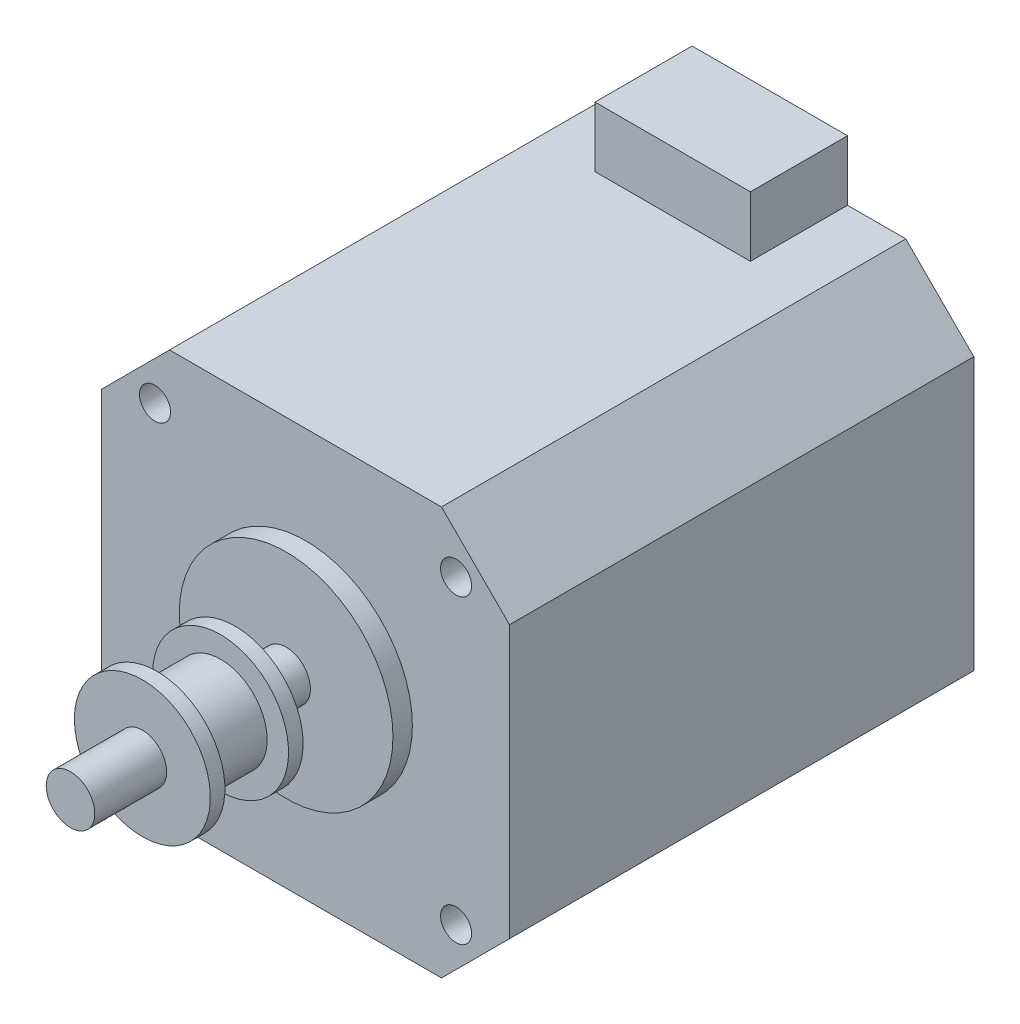
SolidWorks part; units mm, degrees
ref_plane "Front Plane" through (0, 0, 0) normal (0, 0, 1) x (1, 0, 0)
ref_plane "Top Plane" through (0, 0, 0) normal (0, 1, 0) x (1, 0, 0)
ref_plane "Right Plane" through (0, 0, 0) normal (1, 0, 0) x (0, 0, -1)
sketch "Sketch1" plane through (0, 0, 0) normal (0, 0, 1) x (1, 0, 0)
  line L1 (0, 0) -> (42, 0)
  line L2 (0, 0) -> (0, 42)
  line L3 (0, 42) -> (42, 42)
  line L4 (42, 0) -> (42, 42)
  dimension "D1" = 42
extrude "Boss-Extrude1" add sketch "Sketch1" along normal blind 47.8
chamfer "Chamfer1" distance 7 angle 45 4 edges at (42, 0, 23.9) (0, 0, 23.9) (0, 42, 23.9) (42, 42, 23.9)
sketch "Sketch2" plane through (0, 0, 0) normal (0, 0, -1) x (-1, 0, 0)
  line L0 (-35, 42) -> (-7, 42) construction
  line L1 (-29, 42) -> (-13, 42)
  line L2 (-29, 42) -> (-29, 48.2)
  line L3 (-29, 48.2) -> (-13, 48.2)
  line L4 (-13, 42) -> (-13, 48.2)
  line L5 (-21, 0) -> (-21, 4.7739) construction
  line L6 (-7, 0) -> (-35, 0) construction
  point P10 (-21, 48.2)
  dimension "D1" = 16
  dimension "D2" = 6.2
extrude "Boss-Extrude2" add sketch "Sketch2" against normal blind 10
sketch "Sketch3" plane through (0, 0, 47.8) normal (0, 0, 1) x (1, 0, 0)
  line L0 (21, 42) -> (21, 17.1578) construction
  line L1 (35, 42) -> (7, 42) construction
  line L2 (0, 21) -> (27.6359, 21) construction
  line L3 (0, 35) -> (0, 7) construction
  circle A0 centre (21, 21) radius 11
  dimension "D1" = 22
extrude "Boss-Extrude3" add sketch "Sketch3" along normal blind 2
sketch "Sketch4" plane through (0, 0, 47.8) normal (0, 0, 1) x (1, 0, 0)
  line L0 (0, 21) -> (7.2177, 21) construction
  line L1 (0, 35) -> (0, 7) construction
  line L2 (21, 42) -> (21, 37.6441) construction
  line L3 (35, 42) -> (7, 42) construction
  circle A0 centre (5.5, 36.5) radius 1.6
  circle A1 centre (36.5, 36.5) radius 1.6
  circle A2 centre (36.5, 5.5) radius 1.6
  circle A3 centre (5.5, 5.5) radius 1.6
  dimension "D1" = 3.2
  dimension "D2" = 31
  dimension "D3" = 31
  dimension "D4" = 15.5
  dimension "D5" = 15.5
extrude "Cut-Extrude1" cut sketch "Sketch4" against normal blind 3
ref_plane "Plane1" through (0, 21, 0) normal (0, 1, 0) x (1, 0, 0)
sketch "Sketch5" plane through (0, 21, 0) normal (0, 1, 0) x (1, 0, 0)
  line L0 (21, -49.8) -> (21, -72)
  line L1 (10, -49.8) -> (32, -49.8) construction
  line L2 (21, -64.6) -> (28, -64.6)
  line L3 (28, -64.6) -> (28, -63.1)
  line L4 (28, -63.1) -> (25.8, -63.1)
  line L5 (25.8, -63.1) -> (25.8, -56.55)
  line L6 (25.8, -56.55) -> (28, -56.55)
  line L7 (28, -56.55) -> (28, -55.05)
  line L8 (28, -55.05) -> (21, -55.05)
  line L9 (23.5, -49.8) -> (23.5, -72)
  line L10 (23.5, -72) -> (21, -72)
  line L11 (21, -49.8) -> (23.5, -49.8)
  point P6 (26.9, -56.55)
  dimension "D1" = 22.2
  dimension "D2" = 7
  dimension "D3" = 6.55
  dimension "D4" = 4.8
  dimension "D5" = 1.5
  dimension "D6" = 1.5
  dimension "D7" = 7.4
  dimension "D8" = 2.5
revolve "Revolve1" add sketch "Sketch5" angle 360 about L0
sketch "Sketch6" plane through (0, 0, 64.6) normal (0, 0, 1) x (1, 0, 0)
  line L0 (21, 21) -> (28, 21) construction
  line L1 (28, 21) -> (28, 9.0753) construction
  circle A0 centre (21, 21) radius 7 construction
  circle A5 centre (21, 21) radius 2.5 construction
